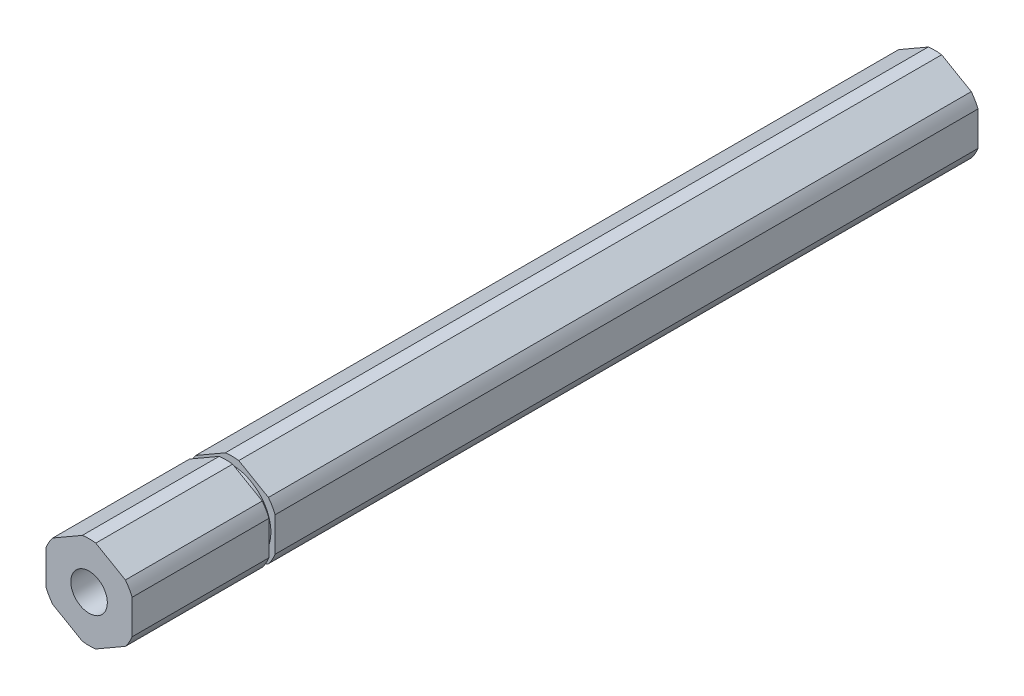
SolidWorks part; units mm, degrees
material "7075-T6 (SN)"
ref_plane "Front Plane" through (0, 0, 0) normal (0, 0, 1) x (1, 0, 0)
ref_plane "Top Plane" through (0, 0, 0) normal (0, 1, 0) x (1, 0, 0)
ref_plane "Right Plane" through (0, 0, 0) normal (1, 0, 0) x (0, 0, -1)
sketch "Sketch1" plane through (0, 0, 0) normal (0, 0, 1) x (1, 0, 0)
  line L1 (4.7625, 2.7496) -> (0, 5.4993)
  line L2 (0, 5.4993) -> (-4.7625, 2.7496)
  line L3 (-4.7625, 2.7496) -> (-4.7625, -2.7496)
  line L4 (-4.7625, -2.7496) -> (0, -5.4993)
  line L5 (0, -5.4993) -> (4.7625, -2.7496)
  line L6 (4.7625, -2.7496) -> (4.7625, 2.7496)
  circle A0 centre (0, 0) radius 4.7625 construction
  circle A1 centre (0, 0) radius 5.1245
  dimension "D1" = 10.2489
  dimension "D2" = 9.525
extrude "Boss-Extrude1" add sketch "Sketch1" along normal mid plane 93.5355 contours L6 A1 L1 L2 L3 L4 L5
sketch "Sketch2" plane through (0, 0, -46.7677) normal (0, 0, -1) x (-1, 0, 0)
  circle A0 centre (0, 0) radius 2.0193
  dimension "D1" = 4.0386
extrude "Cut-Extrude1" cut sketch "Sketch2" against normal blind 19.05
mirror "Mirror1" about plane through (0, 0, 0) normal (0, 0, 1) of "Cut-Extrude1"
sketch "Sketch3" plane through (2.3812, 4.1244, 0) normal (0.5, 0.866, 0) x (0.866, -0.5, 0)
  line L0 (0, 46.7677) -> (0, -35.833) construction
  line L2 (1.8917, 46.7677) -> (-1.8917, 46.7677) construction
  dimension "D1" = 82.6008
ref_plane "Plane1" through (0, 0, 30.9563) normal (0, 0, -1) x (-1, 0, 0)
sketch "Sketch4" plane through (0, 0, 30.9563) normal (0, 0, -1) x (-1, 0, 0)
  circle A0 centre (0, 0) radius 4.2926
  circle A1 centre (0, 0) radius 6.35
  dimension "D1" = 8.5852
  dimension "D2" = 12.7
extrude "Cut-Extrude2" cut sketch "Sketch4" against normal blind 0.6858
